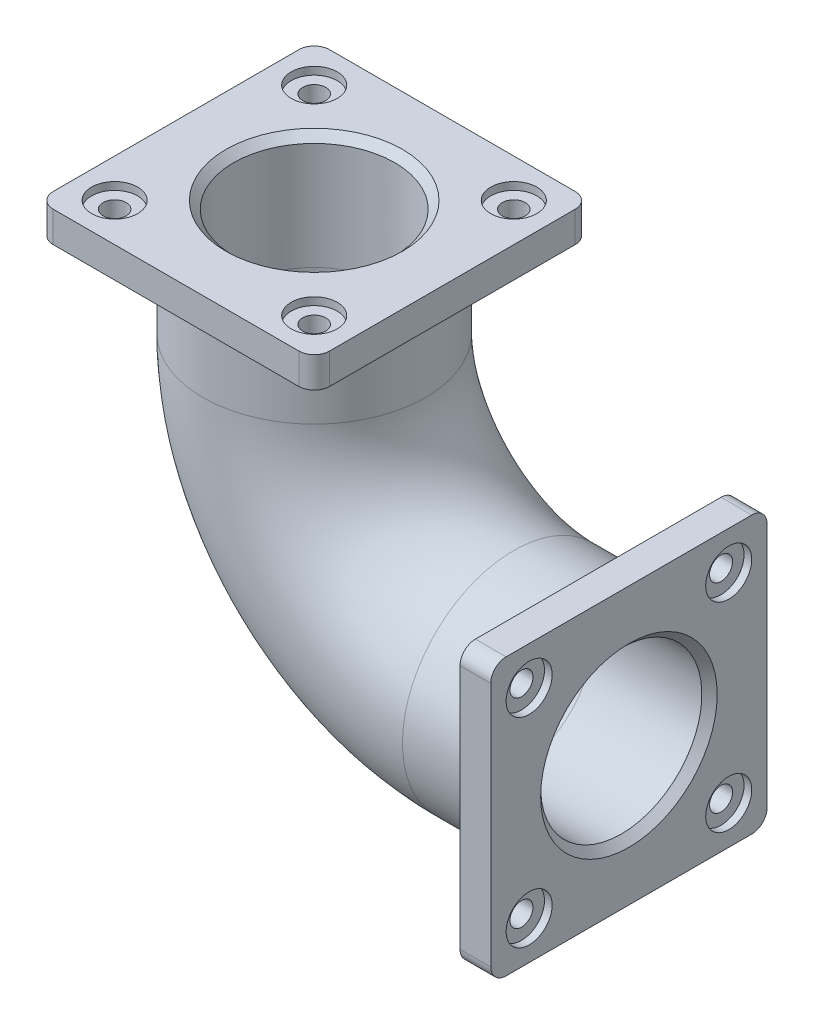
SolidWorks part; units mm, degrees
ref_plane "Front Plane" through (0, 0, 0) normal (0, 0, 1) x (1, 0, 0)
ref_plane "Top Plane" through (0, 0, 0) normal (0, 1, 0) x (1, 0, 0)
ref_plane "Right Plane" through (0, 0, 0) normal (1, 0, 0) x (0, 0, -1)
sketch "Sketch1" plane through (0, 0, 0) normal (0, 0, 1) x (1, 0, 0)
  line L0 (0, 0) -> (-150, 0)
  line L1 (-410, 260) -> (-410, 410)
  arc A0 (-150, 0) -> (-410, 260) centre (-150, 260) cw
  dimension "D2" = 260
  dimension "D1" = 150
sketch "Sketch2" plane through (0, 0, 0) normal (1, 0, 0) x (0, 0, -1)
  circle A0 centre (0, 0) radius 145
  dimension "D1" = 290
sweep "Sweep-Thin1" add profiles "Sketch2" path "Sketch1" parameters "D1"=40
sketch "Sketch3" plane through (0, 0, 0) normal (1, 0, 0) x (0, 0, -1)
  line L1 (-180, 180) -> (180, 180)
  line L2 (-180, 180) -> (-180, -180)
  line L3 (-180, -180) -> (180, -180)
  line L4 (180, 180) -> (180, -180)
  line L5 (-180, 180) -> (180, -180) construction
  line L6 (-180, -180) -> (180, 180) construction
  point P0 (0, 0)
  circle M4 centre (0, 0) radius 145
  dimension "D1" = 360
  dimension "D2" = 360
extrude "Boss-Extrude1" add sketch "Sketch3" against normal blind 40 contours L4 L1 L2 L3 M4
sketch "Sketch4" plane through (0, 410, 0) normal (0, 1, 0) x (1, 0, 0)
  line L1 (-590, 180) -> (-230, 180)
  line L2 (-590, 180) -> (-590, -180)
  line L3 (-590, -180) -> (-230, -180)
  line L4 (-230, 180) -> (-230, -180)
  line L5 (-590, 180) -> (-230, -180) construction
  line L6 (-590, -180) -> (-230, 180) construction
  point P0 (-410, 0)
  circle M4 centre (-410, 0) radius 145
  dimension "D1" = 360
  dimension "D2" = 360
extrude "Boss-Extrude2" add sketch "Sketch4" against normal blind 40 contours L4 L1 L2 L3 M4
fillet "Fillet1" radius 20 8 edges at (-230, 390, -180) (-590, 390, -180) (-590, 390, 180) (-230, 390, 180) (-20, 180, -180) (-20, -180, 180) (-20, -180, -180) (-20, 180, 180)
chamfer "Chamfer1" distance 10 angle 45 2 edges at (0, 0, -105) (-305, 410, 0)
sketch "Sketch5" plane through (0, 0, 0) normal (1, 0, 0) x (0, 0, -1)
  line L1 (-130, 130) -> (130, 130) construction
  line L2 (-130, 130) -> (-130, -130) construction
  line L3 (-130, -130) -> (130, -130) construction
  line L4 (130, 130) -> (130, -130) construction
  line L5 (-130, 130) -> (130, -130) construction
  line L6 (-130, -130) -> (130, 130) construction
  circle A0 centre (-130, 130) radius 30
  point P0 (0, 0)
  dimension "D3" = 60
  dimension "D1" = 260
  dimension "D2" = 260
extrude "Cut-Extrude1" cut sketch "Sketch5" against normal blind 10
sketch "Sketch6" plane through (-10, 0, 0) normal (1, 0, 0) x (0, 0, -1)
  circle A0 centre (-130, 130) radius 15
  dimension "D1" = 30
extrude "Cut-Extrude2" cut sketch "Sketch6" against normal up to next
pattern_circular "CirPattern1" count 4 over 360 about axis through (0, 0, 0) along (1, 0, 0) of "Cut-Extrude1", "Cut-Extrude2"
sketch "Sketch7" plane through (0, 410, 0) normal (0, 1, 0) x (1, 0, 0)
  line L1 (-540, 130) -> (-280, 130) construction
  line L2 (-540, 130) -> (-540, -130) construction
  line L3 (-540, -130) -> (-280, -130) construction
  line L4 (-280, 130) -> (-280, -130) construction
  line L5 (-540, 130) -> (-280, -130) construction
  line L6 (-540, -130) -> (-280, 130) construction
  circle A0 centre (-540, 130) radius 30
  point P0 (-410, 0)
  dimension "D3" = 60
  dimension "D1" = 260
  dimension "D2" = 260
extrude "Cut-Extrude3" cut sketch "Sketch7" against normal blind 10 contours A0
sketch "Sketch8" plane through (0, 400, 0) normal (0, 1, 0) x (1, 0, 0)
  circle A0 centre (-540, 130) radius 15
  dimension "D1" = 30
extrude "Cut-Extrude4" cut sketch "Sketch8" against normal up to next
pattern_circular "CirPattern2" count 4 over 360 about axis through (-410, 0, 0) along (0, 1, 0) of "Cut-Extrude3", "Cut-Extrude4"
